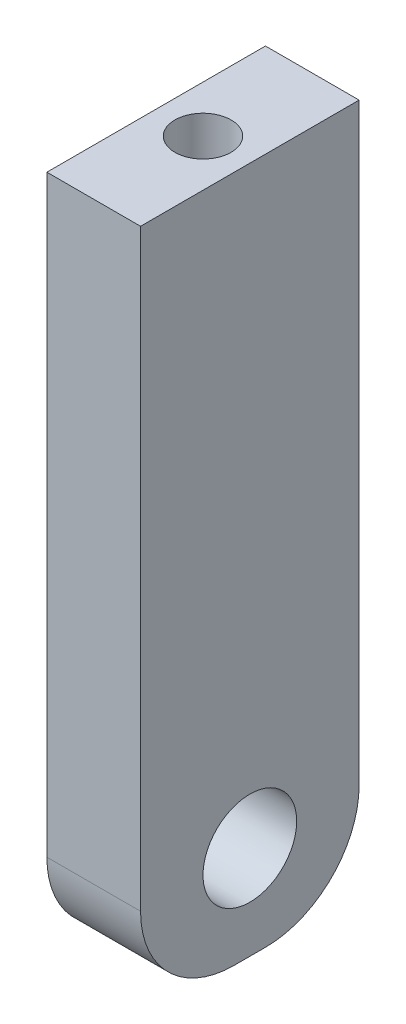
SolidWorks part; units mm, degrees
ref_plane "前视基准面" through (0, 0, 0) normal (0, 0, 1) x (1, 0, 0)
ref_plane "上视基准面" through (0, 0, 0) normal (0, 1, 0) x (1, 0, 0)
ref_plane "右视基准面" through (0, 0, 0) normal (1, 0, 0) x (0, 0, -1)
sketch "草图1" plane through (0, 0, 0) normal (0, 0, 1) x (1, 0, 0)
  line L6 (0, 0.5463) -> (0, -21.4537)
  line L7 (0, -21.4537) -> (3, -21.4537)
  line L8 (3, -21.4537) -> (3, 0.5463)
  line L9 (3, 0.5463) -> (0, 0.5463)
  dimension "D1" = 22
  dimension "D2" = 3
extrude "凸台-拉伸1" add sketch "草图1" along normal blind 7
sketch "草图3" plane through (0, 0.5463, 0) normal (0, 1, 0) x (1, 0, 0)
  line L0 (0, -7) -> (0, 0) construction
  line L1 (3, 0) -> (0, 0) construction
  circle A0 centre (1.5, -3.5) radius 0.9
  point P6 (0, -3.5)
  point P7 (1.5, 0)
  dimension "D1" = 1.8
sketch "草图4" plane through (3, 0, 0) normal (1, 0, 0) x (0, 0, -1)
  line L0 (-7, -21.4537) -> (0, -21.4537) construction
  line L1 (-7, -21.4537) -> (-7, 0.5463) construction
  circle A0 centre (-3.5, -18.4537) radius 1.5
  dimension "D1" = 3
  dimension "D2" = 3
  dimension "D3" = 3.5
extrude "切除-拉伸2" cut sketch "草图4" against normal through all
fillet "圆角1" radius 3 2 edges at (1.5, -21.4537, 7) (1.5, -21.4537, 0)
extrude "切除-拉伸4" cut sketch "草图3" against normal blind 7
